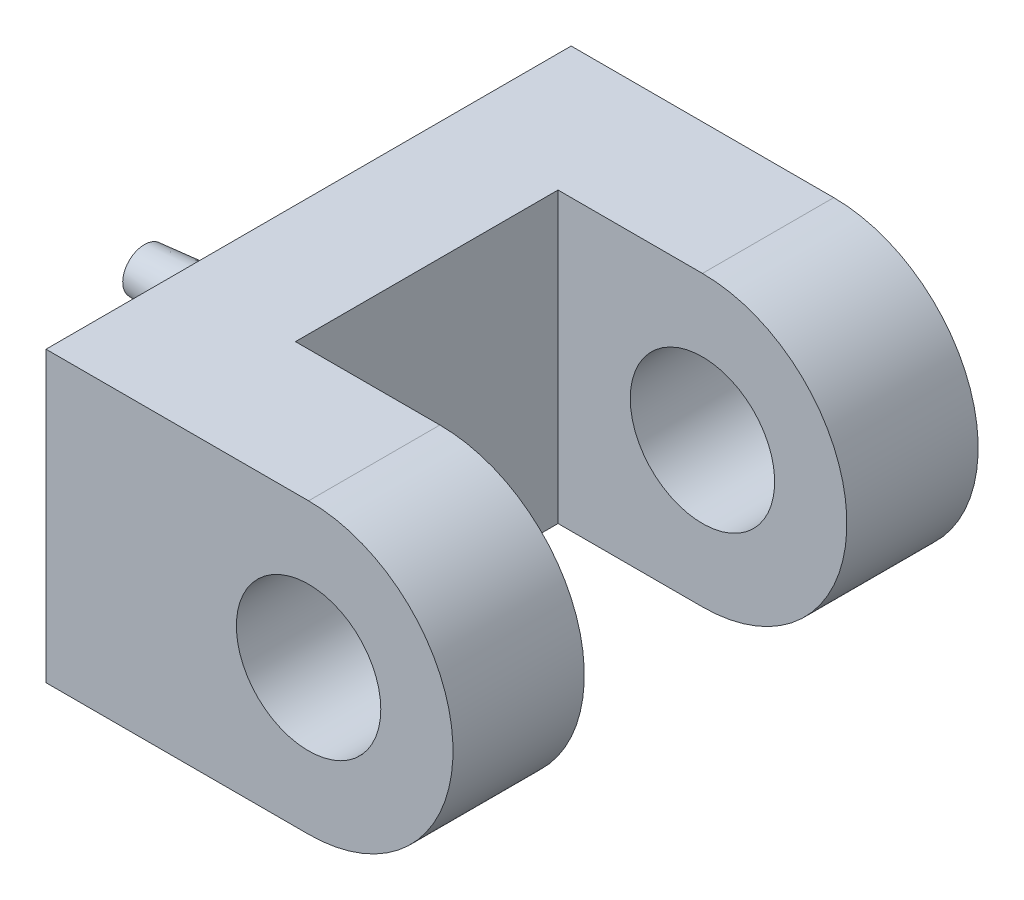
SolidWorks part; units mm, degrees
material "Acrylic (Medium-high impact)"
ref_plane "Front Plane" through (0, 0, 0) normal (0, 0, 1) x (1, 0, 0)
ref_plane "Top Plane" through (0, 0, 0) normal (0, 1, 0) x (1, 0, 0)
ref_plane "Right Plane" through (0, 0, 0) normal (1, 0, 0) x (0, 0, -1)
sketch "Sketch2" plane through (0, 0, 0) normal (0, 0, 1) x (1, 0, 0)
  line L0 (0, 22) -> (-40, 22)
  line L1 (-40, 22) -> (-40, -22)
  line L2 (-40, -22) -> (0, -22)
  circle A0 centre (0, 0) radius 11
  arc A1 (0, 22) -> (0, -22) centre (0, 0) cw
  dimension "D1" = 22
  dimension "D2" = 40
  dimension "16" = 11
extrude "Boss-Extrude1" add sketch "Sketch2" along normal mid plane 80
sketch "Sketch3" plane through (0, 0, 0) normal (0, 1, 0) x (1, 0, 0)
  line L0 (22, -40) -> (22, 40) construction
  line L1 (-22, -20) -> (22, -20)
  line L2 (-22, -20) -> (-22, 20)
  line L3 (-22, 20) -> (22, 20)
  line L4 (22, -20) -> (22, 20)
  line L5 (-22, -20) -> (22, 20) construction
  line L6 (-22, 20) -> (22, -20) construction
  line L7 (22, 40) -> (0, 40) construction
  point P0 (0, 0)
  dimension "D1" = 20
extrude "Cut-Extrude1" cut sketch "Sketch3" against normal through all both and the other way through all
sketch "Sketch4" plane through (-40, 0, 0) normal (-1, 0, 0) x (0, 0, 1)
  circle A0 centre (0, 0) radius 5.5
  dimension "D1" = 11
extrude "Boss-Extrude2" add sketch "Sketch4" along normal blind 25 draft 5
